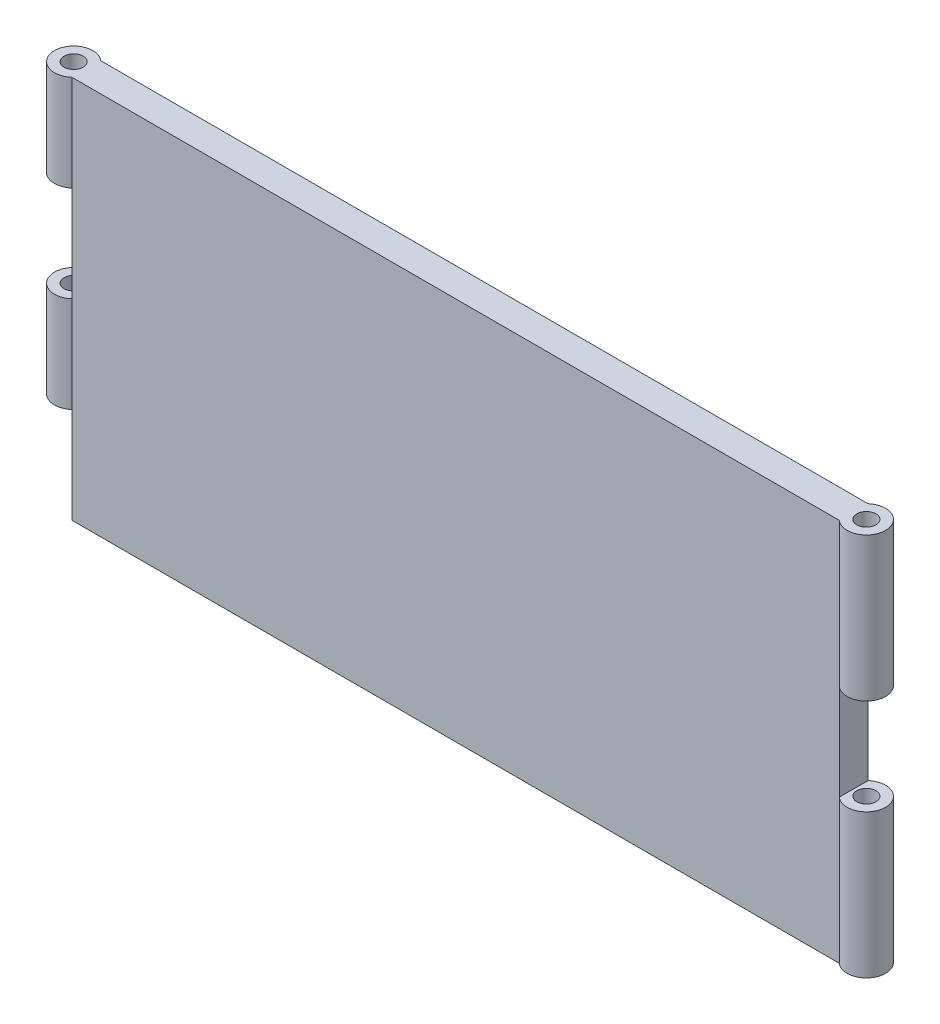
SolidWorks part; units mm, degrees
ref_plane "Front Plane" through (0, 0, 0) normal (0, 0, 1) x (1, 0, 0)
ref_plane "Top Plane" through (0, 0, 0) normal (0, 1, 0) x (1, 0, 0)
ref_plane "Right Plane" through (0, 0, 0) normal (1, 0, 0) x (0, 0, -1)
sketch "Sketch1" plane through (0, 0, 0) normal (0, 0, 1) x (1, 0, 0)
  line L1 (-40, 20) -> (40, 20)
  line L2 (-40, 20) -> (-40, -20)
  line L3 (-40, -20) -> (40, -20)
  line L4 (40, 20) -> (40, -20)
  line L5 (-40, 20) -> (40, -20) construction
  line L6 (-40, -20) -> (40, 20) construction
  point P0 (0, 0)
  dimension "D1" = 80
  dimension "D2" = 40
extrude "Boss-Extrude1" add sketch "Sketch1" along normal blind 3
sketch "Sketch2" plane through (0, 20, 0) normal (0, 1, 0) x (1, 0, 0)
  line L0 (0, 17.6162) -> (0, -25.8952) construction
  circle A0 centre (-41.3229, -1.5) radius 2
  circle A1 centre (-41.3229, -1.5) radius 1
  dimension "D1" = 4
  dimension "D2" = 2
extrude "Boss-Extrude3" add sketch "Sketch2" against normal blind 10
pattern_linear "LPattern1" count 2 spacing 20 along (0, -1, 0) of "Boss-Extrude3"
sketch "Sketch3" plane through (0, 20, 0) normal (0, 1, 0) x (1, 0, 0)
  circle A0 centre (41.3229, -1.5) radius 2
  circle A1 centre (41.3229, -1.5) radius 2
  circle A2 centre (41.3229, -1.5) radius 1
  dimension "D1" = 4
  dimension "D2" = 2
extrude "Boss-Extrude4" add sketch "Sketch3" against normal blind 15 contours A2 | A0
pattern_linear "LPattern2" count 2 spacing 25 along (0, -1, 0) of "Boss-Extrude4"
